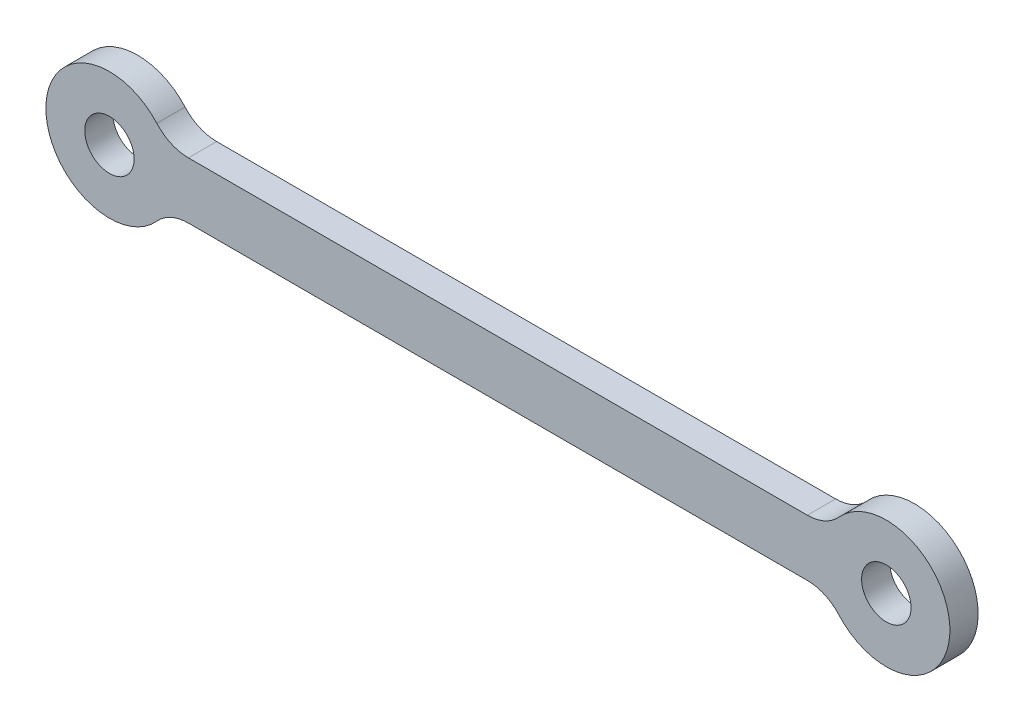
SolidWorks part; units mm, degrees
ref_plane "Front Plane" through (0, 0, 0) normal (0, 0, 1) x (1, 0, 0)
ref_plane "Top Plane" through (0, 0, 0) normal (0, 1, 0) x (1, 0, 0)
ref_plane "Right Plane" through (0, 0, 0) normal (1, 0, 0) x (0, 0, -1)
sketch "Sketch1" plane through (0, 0, 0) normal (0, 0, 1) x (1, 0, 0)
  line L2 (5.5902, 2) -> (49.4098, 2)
  line L3 (4.0311, 2) -> (4.0311, -2) construction
  line L4 (49.4098, -2) -> (5.5902, -2)
  line L5 (50.9689, 2) -> (50.9689, -2) construction
  circle A8 centre (0, 0) radius 1.75
  arc A9 (3.3541, 3) -> (3.3541, -3) centre (0, 0) ccw
  circle A10 centre (55, 0) radius 1.75
  arc A11 (51.6459, -3) -> (51.6459, 3) centre (55, 0) ccw
  arc A12 (51.6459, -3) -> (49.4098, -2) centre (49.4098, -5) ccw
  arc A13 (49.4098, 2) -> (51.6459, 3) centre (49.4098, 5) ccw
  arc A14 (5.5902, -2) -> (3.3541, -3) centre (5.5902, -5) ccw
  arc A15 (5.5902, 2) -> (3.3541, 3) centre (5.5902, 5) cw
  dimension "D3" = 4.5
  dimension "D5" = 3.5
  dimension "D6" = 3.5
  dimension "D7" = 4.5
  dimension "D9" = 3
  dimension "D2" = 4
  dimension "D8" = 55
extrude "Boss-Extrude1" add sketch "Sketch1" along normal blind 2
